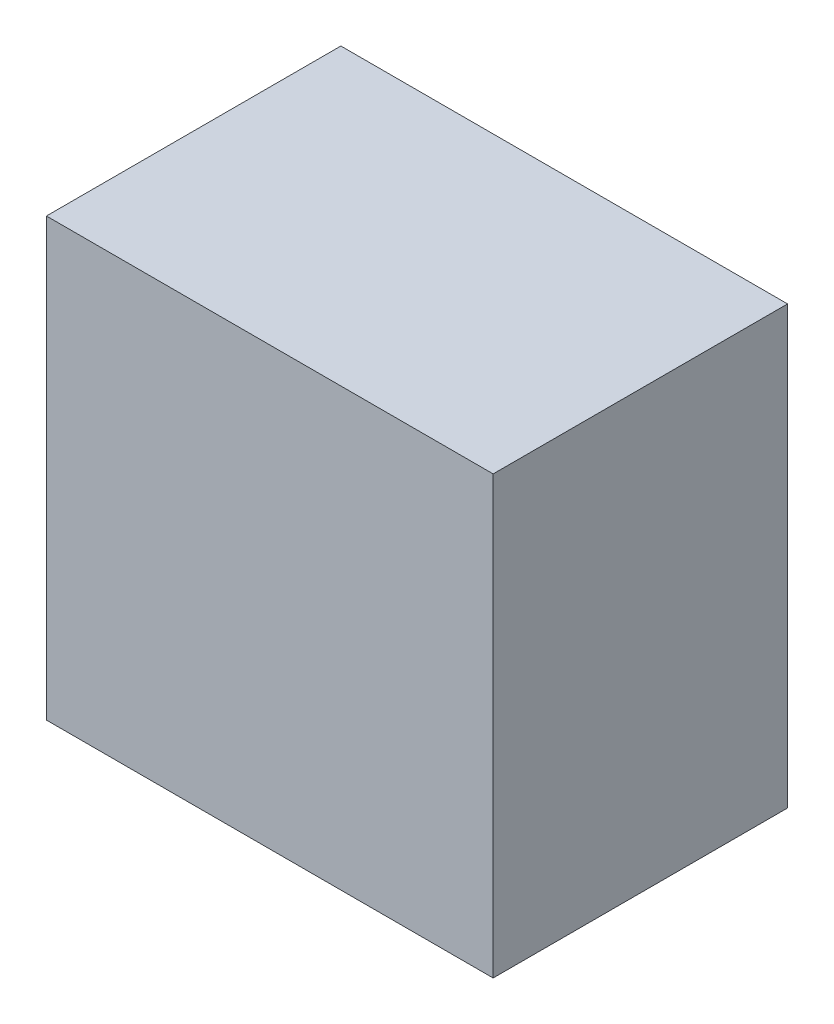
SolidWorks part; units mm, degrees
ref_plane "Front Plane" through (0, 0, 0) normal (0, 0, 1) x (1, 0, 0)
ref_plane "Top Plane" through (0, 0, 0) normal (0, 1, 0) x (1, 0, 0)
ref_plane "Right Plane" through (0, 0, 0) normal (1, 0, 0) x (0, 0, -1)
sketch "Sketch1" plane through (0, 0, 0) normal (0, 0, 1) x (1, 0, 0)
  line L1 (0, 0) -> (88, 0)
  line L2 (0, 0) -> (0, 86)
  line L3 (0, 86) -> (88, 86)
  line L4 (88, 0) -> (88, 86)
  dimension "D1" = 88
  dimension "D2" = 86
extrude "Boss-Extrude1" add sketch "Sketch1" against normal blind 58
